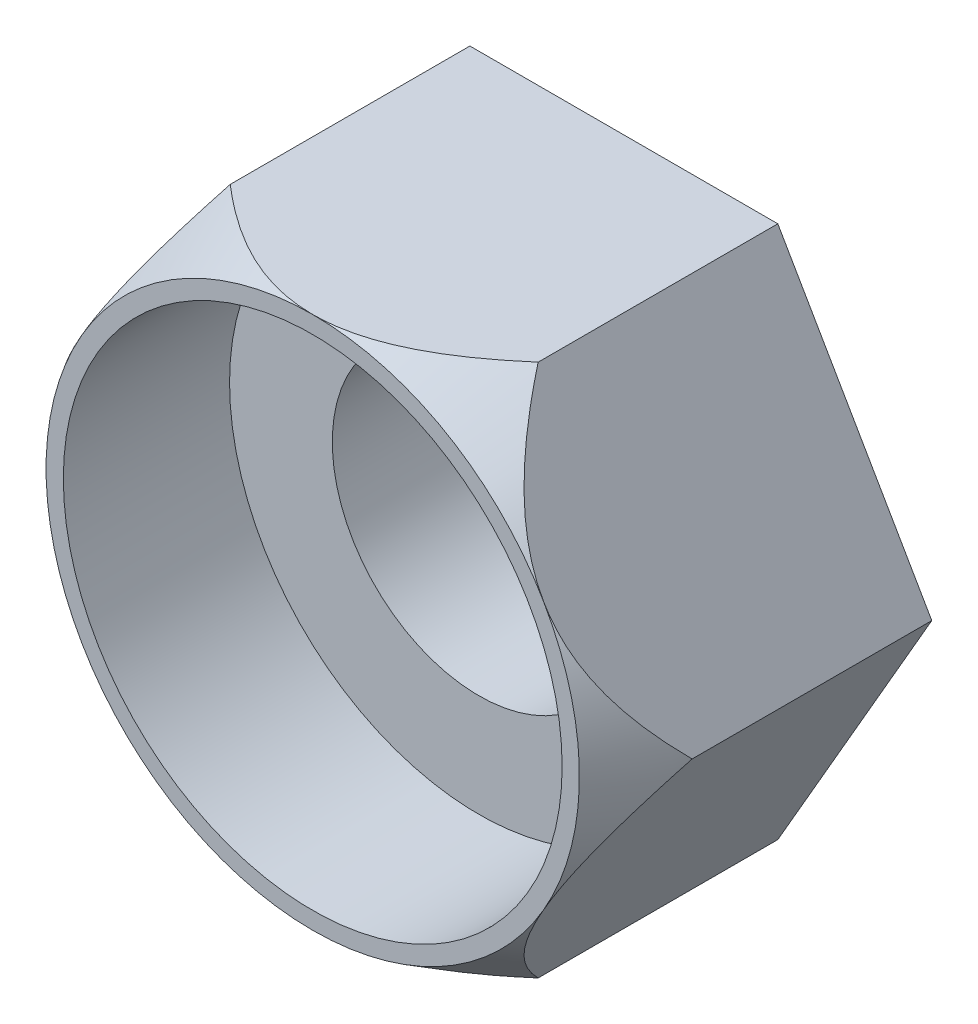
SolidWorks part; units mm, degrees
ref_plane "Front Plane" through (0, 0, 0) normal (0, 0, 1) x (1, 0, 0)
ref_plane "Top Plane" through (0, 0, 0) normal (0, 1, 0) x (1, 0, 0)
ref_plane "Right Plane" through (0, 0, 0) normal (1, 0, 0) x (0, 0, -1)
sketch "Sketch2" plane through (0, 0, 0) normal (0, 0, 1) x (1, 0, 0)
  line L1 (34.641, 0) -> (17.3205, 30)
  line L2 (17.3205, 30) -> (-17.3205, 30)
  line L3 (-17.3205, 30) -> (-34.641, 0)
  line L4 (-34.641, 0) -> (-17.3205, -30)
  line L5 (-17.3205, -30) -> (17.3205, -30)
  line L6 (17.3205, -30) -> (34.641, 0)
  circle A0 centre (0, 0) radius 30 construction
extrude "Boss-Extrude1" add sketch "Sketch2" along normal mid plane 35
sketch "Sketch3" plane through (0, 0, 17.5) normal (0, 0, 1) x (1, 0, 0)
  circle A0 centre (0, 0) radius 30
extrude "Cut-Extrude1" cut sketch "Sketch3" against normal mid plane 35 draft 30 flip side to cut
hole_wizard "CBORE for M30 Hex Head Bolt1" positions "Sketch4" profile "Sketch5" counterbore size "M30" standard "ISO" end condition through all
sketch "Sketch4" plane through (0, 0, 17.5) normal (0, 0, 1) x (1, 0, 0)
  point P0 (0, 0)
sketch "Sketch5" plane through (0, 0, 17.5) normal (1, 0, 0) x (0, -1, 0)
  line L0 (0, 0) -> (0, 35)
  line L1 (0, 35) -> (16.5, 35)
  line L3 (16.5, 35) -> (16.5, 18.7)
  line L4 (16.5, 18.7) -> (28.058, 18.7)
  line L5 (28.058, 18.7) -> (28.058, 0)
  line L7 (28.058, 0) -> (0, 0)
  line L11 (0, -6.35) -> (0, 107.95) construction
  dimension "Thru Hole Dia." = 33
  dimension "Thru Hole Depth" = 35
  dimension "C'Bore Dia." = 56.116
  dimension "C'Bore Depth" = 18.7
